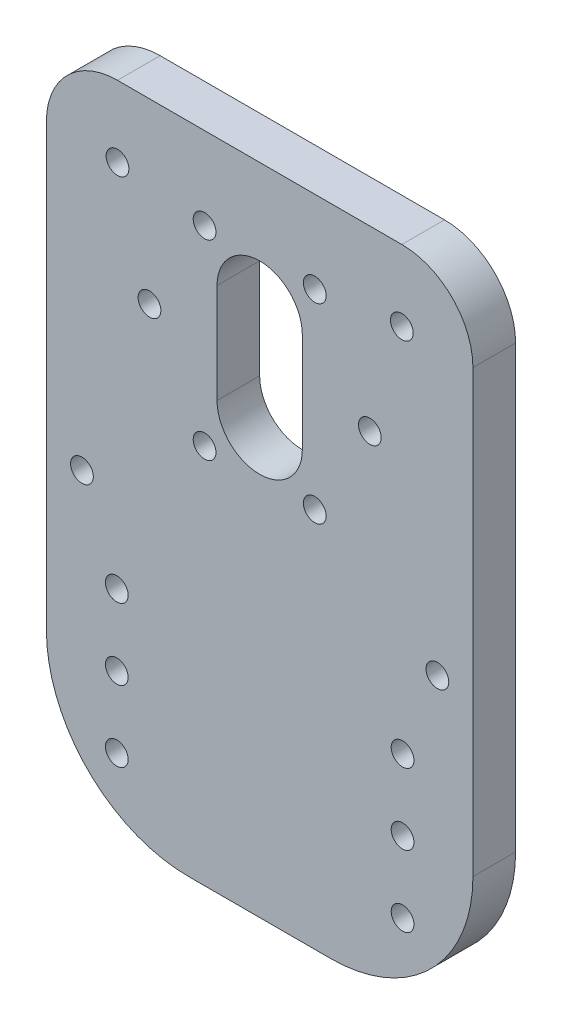
SolidWorks part; units mm, degrees
ref_plane "前视基准面" through (0, 0, 0) normal (0, 0, 1) x (1, 0, 0)
ref_plane "上视基准面" through (0, 0, 0) normal (0, 1, 0) x (1, 0, 0)
ref_plane "右视基准面" through (0, 0, 0) normal (1, 0, 0) x (0, 0, -1)
other "Configuration Table"
sketch "草图1" plane through (0, 0, 0) normal (0, 0, 1) x (1, 0, 0)
  line L0 (0, -60) -> (0, -50)
  line L5 (-30, -60) -> (30, -60)
  line L6 (-30, -60) -> (-30, 60)
  line L7 (0, -50) -> (20, -50)
  line L8 (-30, 60) -> (30, 60)
  line L9 (30, -60) -> (30, 60)
  line L10 (-30, -60) -> (30, 60) construction
  line L11 (-30, 60) -> (30, -60) construction
  line L12 (0, 60) -> (0, 10)
  line L13 (0, 35) -> (0, 42)
  line L14 (0, 42) -> (0, 28) construction
  line L15 (6, 42) -> (6, 28)
  line L16 (-6, 42) -> (-6, 28)
  circle A33 centre (0, 50.5) radius 1.6
  circle A34 centre (20, -50) radius 2.15
  circle A35 centre (-20, -50) radius 2.15
  circle A36 centre (0, 35) radius 19
  circle A37 centre (0, 35) radius 15.5
  circle A38 centre (13.4234, 42.75) radius 1.6
  circle A39 centre (13.4234, 27.25) radius 1.6
  circle A40 centre (0, 19.5) radius 1.6
  circle A41 centre (-13.4234, 27.25) radius 1.6
  circle A42 centre (-13.4234, 42.75) radius 1.6
  arc A43 (6, 42) -> (-6, 42) centre (0, 42) ccw
  arc A44 (-6, 28) -> (6, 28) centre (0, 28) ccw
  point P0 (0, 0)
  point P20 (0, 35)
  dimension "D5" = 4.3
  dimension "D8" = 31
  dimension "D9" = 3.2
  dimension "D10" = 6
  dimension "D13" = 6
  dimension "D7" = 38
  dimension "D1" = 60
  dimension "D2" = 120
  dimension "D3" = 10
  dimension "D4" = 20
  dimension "D6" = 50
  dimension "D11" = 7
  dimension "D12" = 14
extrude "凸台-拉伸3" add sketch "草图1" along normal blind 6
sketch "草图9" plane through (0, 0, 6) normal (0, 0, 1) x (1, 0, 0)
  line L0 (0, -972) -> (0, 49028) construction
  line L1 (-15, 28) -> (-15, -12)
  line L2 (-15, -12) -> (-20.1, -12)
  line L3 (-20, 28) -> (-20.1, -22)
  line L4 (-20.1, -22) -> (-25.1, -22)
  circle A0 centre (0, 28) radius 15
  circle A2 centre (-20.1, -12) radius 1.6
  circle A3 centre (20.1, -12) radius 1.6
  circle A4 centre (0, 28) radius 20
  circle A7 centre (-20.1, -2) radius 1.6
  circle A8 centre (20.1, -2) radius 1.6
  circle A13 centre (-20.1, -22) radius 1.6
  circle A14 centre (20.1, -22) radius 1.6
  dimension "D1" = 30
  dimension "D3" = 5.1
  dimension "D4" = 3.2
  dimension "D5" = 40
  dimension "D8" = 2
  dimension "D2" = 40
  dimension "D6" = 50
  dimension "D7" = 5
  dimension "D9" = 2
extrude "切除-拉伸1" cut sketch "草图9" against normal blind 6 contours A14 | A8 | A3 | A7 | A2 | A13
fillet "圆角1" radius 10 4 edges at (30, -60, 3) (-30, -60, 3) (30, 60, 3) (-30, 60, 3)
sketch "草图11" plane through (0, 0, 6) normal (0, 0, 1) x (1, 0, 0)
  line L0 (-20.1, -22) -> (-30, -22)
  line L1 (-30, -50) -> (-30, 50) construction
  line L2 (-30, -22) -> (-30, -32)
  line L3 (30.1, -70) -> (30.1, -60) construction
  line L4 (-30, -32) -> (30.1, -32)
  line L5 (-30, -32) -> (-30, -63.0814)
  line L6 (-30, -63.0814) -> (30.1, -63.0814)
  line L7 (30.1, -32) -> (30.1, -63.0814)
  circle M19 centre (20, -50) radius 2.15
  line M20 (-20, -60) -> (20, -60)
  arc M21 (20, -60) -> (30, -50) centre (20, -50) ccw
  line M22 (30, -50) -> (30, 50)
  line M26 (-30, 50) -> (-30, -50)
  arc M27 (-30, -50) -> (-20, -60) centre (-20, -50) ccw
  circle M28 centre (-20, -50) radius 2.15
  dimension "D1" = 10
extrude "切除-拉伸2" cut sketch "草图11" against normal blind 6 contours L4 M26 M27 M20 M21 M22 M19 M28
fillet "圆角2" radius 20 2 edges at (30, -32, 3) (-30, -32, 3)
sketch "草图12" plane through (0, 0, 0) normal (0, 0, -1) x (-1, 0, 0)
  circle A0 centre (-20, 50) radius 1.6
  circle A1 centre (20, 50) radius 1.6
  circle A2 centre (25, 10) radius 1.6
  circle A3 centre (-25, 10) radius 1.6
extrude "切除-拉伸3" cut sketch "草图12" against normal blind 10
sketch "草图13" plane through (0, 0, 6) normal (0, 0, 1) x (1, 0, 0)
  line L0 (-1000, 35) -> (49000, 35) construction
  circle A1 centre (-15.5, 35) radius 1.6
  circle A2 centre (-7.75, 48.4234) radius 1.6
  circle A3 centre (7.75, 48.4234) radius 1.6
  circle A4 centre (15.5, 35) radius 1.6
  circle A5 centre (7.75, 21.5766) radius 1.6
  circle A6 centre (-7.75, 21.5766) radius 1.6
  dimension "D1" = 3.2
  dimension "D2" = 6
extrude "切除-拉伸4" cut sketch "草图13" against normal blind 10
sketch "草图14" plane through (0, 0, 6) normal (0, 0, 1) x (1, 0, 0)
  circle A1 centre (0, 50.5) radius 1.6
  circle A2 centre (13.4234, 42.75) radius 1.6
  circle A3 centre (13.4234, 27.25) radius 1.6
  circle A4 centre (0, 19.5) radius 1.6
  circle A5 centre (-13.4234, 27.25) radius 1.6
  circle A6 centre (-13.4234, 42.75) radius 1.6
  dimension "D1" = 6
extrude "凸台-拉伸5" add sketch "草图14" against normal blind 6
